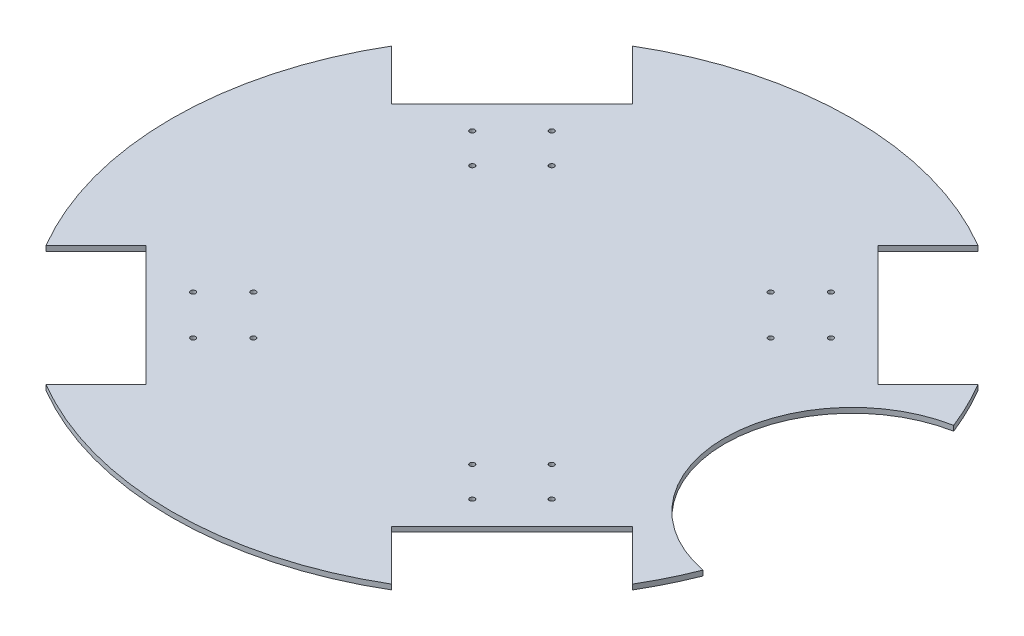
SolidWorks part; units mm, degrees
ref_plane "Front Plane" through (0, 0, 0) normal (0, 0, 1) x (1, 0, 0)
ref_plane "Top Plane" through (0, 0, 0) normal (0, 1, 0) x (1, 0, 0)
ref_plane "Right Plane" through (0, 0, 0) normal (1, 0, 0) x (0, 0, -1)
sketch "Sketch1" plane through (0, 0, 0) normal (0, 1, 0) x (1, 0, 0)
  circle A0 centre (0, 0) radius 200
  dimension "D1" = 400
extrude "Boss-Extrude1" add sketch "Sketch1" along normal blind 3 contours A0
sketch "Sketch2" plane through (0, 3, 0) normal (0, 1, 0) x (1, 0, 0)
  line L0 (-200, 0) -> (200, 0) construction
  line L1 (0, 200) -> (0, -200) construction
  line L2 (0, 0) -> (141.4214, 141.4214) construction
  line L3 (0, 0) -> (-141.4214, 141.4214) construction
  line L4 (0, 0) -> (141.4214, -141.4214) construction
  line L5 (0, 0) -> (-141.4214, -141.4214) construction
  line L6 (231.2643, 160.5537) -> (-164.7889, -235.4996) construction
  line L7 (160.5537, 231.2643) -> (-235.4996, -164.7889) construction
  line L8 (231.2643, -160.5537) -> (-164.7889, 235.4996) construction
  line L9 (160.5537, -231.2643) -> (-235.4996, 164.7889) construction
  line L10 (-160.5537, -231.2643) -> (235.4996, 164.7889) construction
  line L11 (-231.2643, -160.5537) -> (164.7889, 235.4996) construction
  line L12 (-231.2643, 160.5537) -> (164.7889, -235.4996) construction
  line L13 (-160.5537, 231.2643) -> (235.4996, -164.7889) construction
  line L14 (-142.8852, -72.1745) -> (-72.1745, -142.8852)
  line L15 (-142.8852, -72.1745) -> (-226.7797, -156.069)
  line L16 (-72.1745, -142.8852) -> (-156.069, -226.7797)
  line L17 (-226.7797, -156.069) -> (-156.069, -226.7797)
  line L18 (-72.1745, 142.8852) -> (-142.8852, 72.1745)
  line L19 (-72.1745, 142.8852) -> (-156.069, 226.7797)
  line L20 (-156.069, 226.7797) -> (-226.7797, 156.069)
  line L21 (-142.8852, 72.1745) -> (-226.7797, 156.069)
  line L22 (142.8852, 72.1745) -> (72.1745, 142.8852)
  line L23 (142.8852, 72.1745) -> (226.7797, 156.069)
  line L24 (226.7797, 156.069) -> (156.069, 226.7797)
  line L25 (72.1745, 142.8852) -> (156.069, 226.7797)
  line L26 (72.1745, -142.8852) -> (142.8852, -72.1745)
  line L27 (72.1745, -142.8852) -> (156.069, -226.7797)
  line L28 (156.069, -226.7797) -> (226.7797, -156.069)
  line L29 (142.8852, -72.1745) -> (226.7797, -156.069)
  circle A0 centre (0, 0) radius 200 construction
  point P31 (0, 0)
  point P48 (0, 0)
  dimension "D1" = 45
  dimension "D2" = 50
  dimension "D3" = 4
  dimension "D4" = 4
extrude "Cut-Extrude1" cut sketch "Sketch2" against normal blind 3
sketch "Sketch3" plane through (0, 3, 0) normal (0, 1, 0) x (1, 0, 0)
  line L0 (0, 0) -> (0, 200) construction
  line L1 (125, 0) -> (125, 247.8272) construction
  circle A0 centre (200, 0) radius 75
  arc A1 (172.286, -101.5753) -> (172.286, 101.5753) centre (0, 0) ccw construction
  arc A2 (101.5753, 172.286) -> (-101.5753, 172.286) centre (0, 0) ccw construction
  dimension "D1" = 150
extrude "Cut-Extrude2" cut sketch "Sketch3" against normal blind 10
sketch "Sketch5" plane through (0, 3, 0) normal (0, 1, 0) x (1, 0, 0)
  line L0 (0, 200) -> (0, -200) construction
  line L1 (125, 0) -> (-200, 0) construction
  line L2 (107.5298, -107.5298) -> (0, 0) construction
  line L3 (142.8852, -72.1745) -> (72.1745, -142.8852) construction
  line L4 (-158.5182, 135.1837) -> (223.4, -246.7346) construction
  line L5 (-135.1837, 158.5182) -> (246.7346, -223.4) construction
  line L6 (-107.5298, -107.5298) -> (107.5298, 107.5298) construction
  line L7 (-72.1745, -142.8852) -> (-142.8852, -72.1745) construction
  line L8 (72.1745, 142.8852) -> (142.8852, 72.1745) construction
  line L9 (137.7942, -31.9114) -> (35.924, -133.7817) construction
  arc A0 (101.5753, 172.286) -> (-101.5753, 172.286) centre (0, 0) ccw construction
  arc A1 (-101.5753, -172.286) -> (101.5753, -172.286) centre (0, 0) ccw construction
  arc A2 (185.9375, 73.6698) -> (185.9375, -73.6698) centre (200, 0) ccw construction
  arc A3 (-172.286, 101.5753) -> (-172.286, -101.5753) centre (0, 0) ccw construction
  circle A4 centre (82.0315, -105.366) radius 1.5
  circle A5 centre (64.3396, -87.6742) radius 1.5
  circle A6 centre (105.366, -82.0315) radius 1.5
  circle A7 centre (87.6742, -64.3396) radius 1.5
  circle A8 centre (-87.6742, -64.3396) radius 1.5
  circle A9 centre (-105.366, -82.0315) radius 1.5
  circle A10 centre (-82.0315, -105.366) radius 1.5
  circle A11 centre (-64.3396, -87.6742) radius 1.5
  circle A12 centre (-64.3396, 87.6742) radius 1.5
  circle A13 centre (-82.0315, 105.366) radius 1.5
  circle A14 centre (-105.366, 82.0315) radius 1.5
  circle A15 centre (-87.6742, 64.3396) radius 1.5
  circle A16 centre (87.6742, 64.3396) radius 1.5
  circle A17 centre (105.366, 82.0315) radius 1.5
  circle A18 centre (82.0315, 105.366) radius 1.5
  circle A19 centre (64.3396, 87.6742) radius 1.5
  point P67 (0, 0)
  dimension "D2" = 120
  dimension "D1" = 16.5
  dimension "D3" = 12.51
  dimension "D4" = 4
extrude "Cut-Extrude4" cut sketch "Sketch5" against normal blind 73
